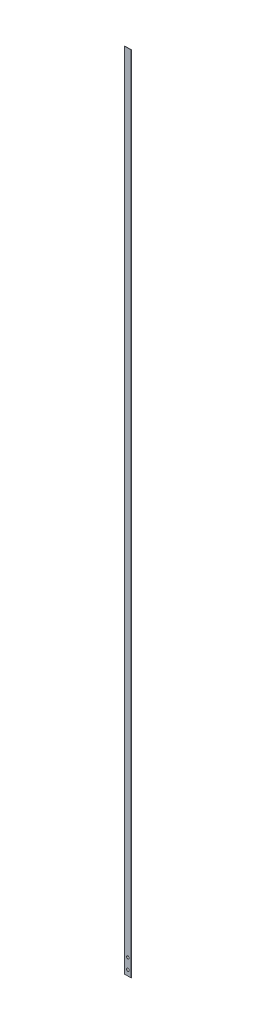
SolidWorks part; units mm, degrees
ref_plane "Front Plane" through (0, 0, 0) normal (0, 0, 1) x (1, 0, 0)
ref_plane "Top Plane" through (0, 0, 0) normal (0, 1, 0) x (1, 0, 0)
ref_plane "Right Plane" through (0, 0, 0) normal (1, 0, 0) x (0, 0, -1)
sketch "Sketch1" plane through (0, 0, 0) normal (0, 1, 0) x (1, 0, 0)
  line L1 (-2.5, -0.1) -> (2.5, -0.1)
  line L2 (-2.5, -0.1) -> (-2.5, 0.1)
  line L3 (-2.5, 0.1) -> (2.5, 0.1)
  line L4 (2.5, -0.1) -> (2.5, 0.1)
  line L5 (-2.5, -0.1) -> (2.5, 0.1) construction
  line L6 (-2.5, 0.1) -> (2.5, -0.1) construction
  point P0 (0, 0)
  dimension "D1" = 5
  dimension "D2" = 0.2
extrude "Boss-Extrude1" add sketch "Sketch1" along normal blind 600
sketch "Sketch2" plane through (0, 0, -0.1) normal (0, 0, -1) x (-1, 0, 0)
  line L0 (2.5, 600) -> (2.5, 0) construction
  line L1 (-2.5, 0) -> (2.5, 0) construction
  circle A0 centre (0, 14) radius 1
  circle A1 centre (0, 6) radius 1
  dimension "D1" = 2
  dimension "D2" = 2
  dimension "D3" = 2.5
  dimension "D4" = 8
  dimension "D5" = 6
extrude "Cut-Extrude1" cut sketch "Sketch2" against normal through all
sketch "Sketch3" plane through (0, 0, 0.1) normal (0, 0, 1) x (1, 0, 0)
  line L0 (2.5, 600) -> (2.5, 0) construction
  line L1 (-2.5, 0) -> (2.5, 0)
  line L2 (-2.5, 0) -> (-2.5, 2)
  line L3 (-2.5, 2) -> (2.5, 2)
  line L4 (2.5, 0) -> (2.5, 2)
  dimension "D1" = 2
extrude "Cut-Extrude2" cut sketch "Sketch3" against normal up to next
